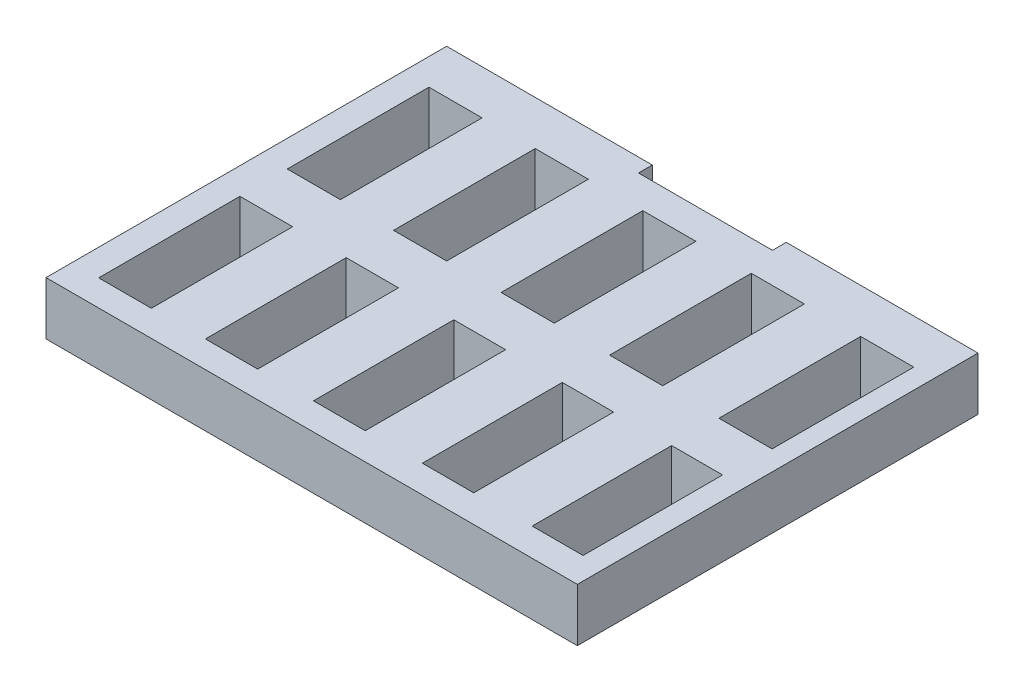
SolidWorks part; units mm, degrees
ref_plane "Front Plane" through (0, 0, 0) normal (0, 0, 1) x (1, 0, 0)
ref_plane "Top Plane" through (0, 0, 0) normal (0, 1, 0) x (1, 0, 0)
ref_plane "Right Plane" through (0, 0, 0) normal (1, 0, 0) x (0, 0, -1)
sketch "Sketch1" plane through (0, 0, 0) normal (0, 1, 0) x (1, 0, 0)
  line L1 (0, 0) -> (60, 0)
  line L2 (0, 0) -> (0, 60)
  line L3 (0, 60) -> (60, 60)
  line L4 (60, 0) -> (60, 60)
  dimension "D1" = 60
  dimension "D2" = 60
extrude "Boss-Extrude1" add sketch "Sketch1" along normal blind 6
sketch "Sketch2" plane through (0, 6, 0) normal (0, 1, 0) x (1, 0, 0)
  line L0 (0, 60) -> (0, 0) construction
  line L1 (3, 55) -> (9, 55)
  line L2 (3, 55) -> (3, 39)
  line L3 (3, 39) -> (9, 39)
  line L4 (9, 55) -> (9, 39)
  line L5 (60, 60) -> (0, 60) construction
  line L7 (15, 55) -> (21, 55)
  line L8 (15, 55) -> (15, 39)
  line L9 (15, 39) -> (21, 39)
  line L10 (21, 55) -> (21, 39)
  line L11 (27.15, 55) -> (33.15, 55)
  line L12 (27.15, 55) -> (27.15, 39)
  line L13 (27.15, 39) -> (33.15, 39)
  line L14 (33.15, 55) -> (33.15, 39)
  line L15 (39.4, 55) -> (45.4, 55)
  line L16 (39.4, 55) -> (39.4, 39)
  line L17 (39.4, 39) -> (45.4, 39)
  line L18 (45.4, 55) -> (45.4, 39)
  line L19 (51.75, 55) -> (57.75, 55)
  line L20 (51.75, 55) -> (51.75, 39)
  line L21 (51.75, 39) -> (57.75, 39)
  line L22 (57.75, 55) -> (57.75, 39)
  line L23 (3, 33.6575) -> (8.95, 33.6575)
  line L24 (3, 33.6575) -> (3, 17.7075)
  line L25 (3, 17.7075) -> (8.95, 17.7075)
  line L26 (8.95, 33.6575) -> (8.95, 17.7075)
  line L27 (15, 33.6575) -> (20.9, 33.6575)
  line L28 (15, 33.6575) -> (15, 17.7575)
  line L29 (15, 17.7575) -> (20.9, 17.7575)
  line L30 (20.9, 33.6575) -> (20.9, 17.7575)
  line L35 (27.15, 33.6575) -> (33, 33.6575)
  line L36 (27.15, 33.6575) -> (27.15, 17.8075)
  line L37 (27.15, 17.8075) -> (33, 17.8075)
  line L38 (33, 33.6575) -> (33, 17.8075)
  line L39 (39.4, 33.6575) -> (45.2, 33.6575)
  line L40 (39.4, 33.6575) -> (39.4, 17.8575)
  line L41 (39.4, 17.8575) -> (45.2, 17.8575)
  line L42 (45.2, 33.6575) -> (45.2, 17.8575)
  line L43 (51.75, 33.6575) -> (57.5, 33.6575)
  line L44 (51.75, 33.6575) -> (51.75, 17.9075)
  line L45 (51.75, 17.9075) -> (57.5, 17.9075)
  line L46 (57.5, 33.6575) -> (57.5, 17.9075)
  dimension "D1" = 3
  dimension "D2" = 5
  dimension "D3" = 16
  dimension "D4" = 6
  dimension "D5" = 6
  dimension "D6" = 6
  dimension "D7" = 6
  dimension "D8" = 0
  dimension "D9" = 6.15
  dimension "D10" = 6
  dimension "D11" = 6.25
  dimension "D12" = 6.35
  dimension "D13" = 6
  dimension "D14" = 5.95
  dimension "D15" = 15.95
  dimension "D16" = 5.9
  dimension "D17" = 5.85
  dimension "D18" = 5.8
  dimension "D19" = 5.75
  dimension "D20" = 15.9
  dimension "D21" = 15.85
  dimension "D22" = 15.8
  dimension "D23" = 15.75
extrude "Cut-Extrude1" cut sketch "Sketch2" against normal blind 6
sketch "Sketch3" plane through (0, 6, 0) normal (0, 1, 0) x (1, 0, 0)
  line L0 (60, 60) -> (0, 60) construction
  line L1 (23.2216, 60) -> (38.3502, 60)
  line L2 (23.2216, 60) -> (23.2216, 58.4419)
  line L3 (23.2216, 58.4419) -> (38.3502, 58.4419)
  line L4 (38.3502, 60) -> (38.3502, 58.4419)
extrude "Cut-Extrude2" cut sketch "Sketch3" against normal blind 6
sketch "Sketch4" plane through (0, 6, 0) normal (0, 1, 0) x (1, 0, 0)
  line L0 (60, 0) -> (60, 60) construction
  line L1 (0, 0) -> (60, 0)
  line L2 (0, 0) -> (0, 14.7575)
  line L3 (0, 14.7575) -> (60, 14.7575)
  line L4 (60, 0) -> (60, 14.7575)
  line L5 (15, 17.7575) -> (20.9, 17.7575) construction
  dimension "D1" = 3
extrude "Cut-Extrude3" cut sketch "Sketch4" against normal blind 6
